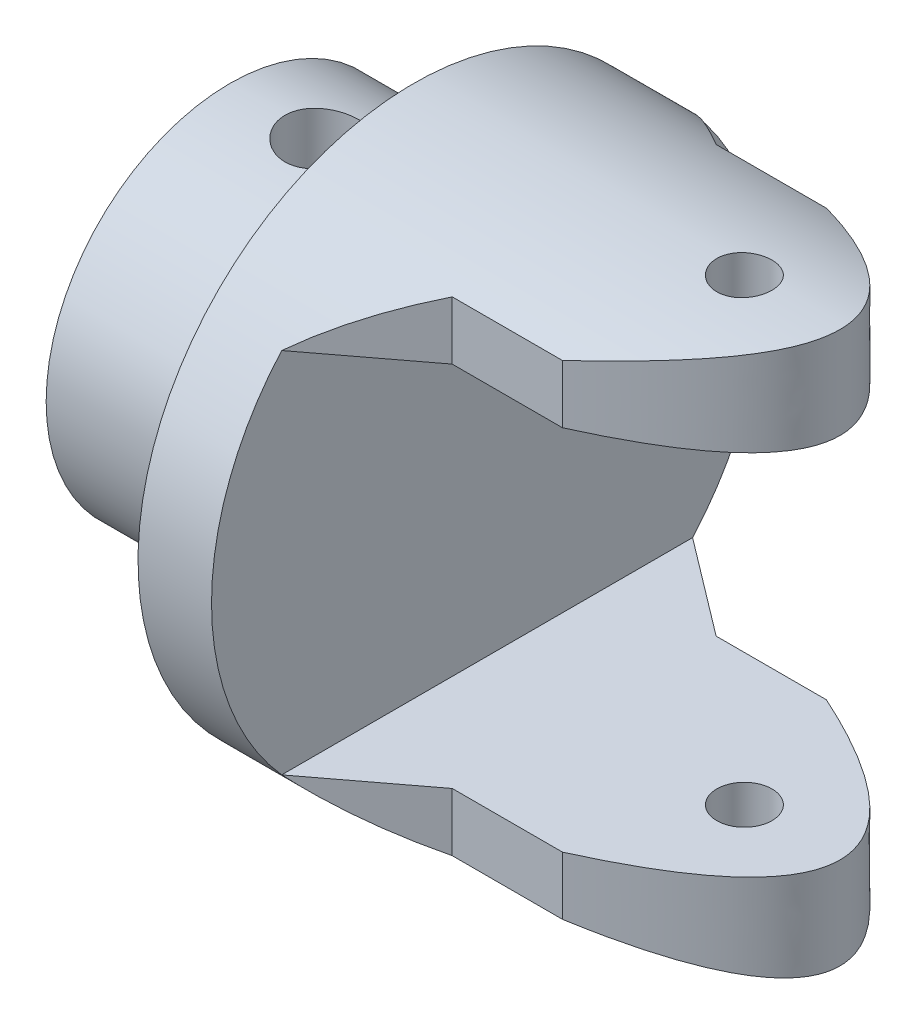
SolidWorks part; units mm, degrees
ref_plane "Front Plane" through (0, 0, 0) normal (0, 0, 1) x (1, 0, 0)
ref_plane "Top Plane" through (0, 0, 0) normal (0, 1, 0) x (1, 0, 0)
ref_plane "Right Plane" through (0, 0, 0) normal (1, 0, 0) x (0, 0, -1)
sketch "Sketch1" plane through (0, 0, 0) normal (1, 0, 0) x (0, 0, -1)
  circle A0 centre (0, 0) radius 5
  dimension "D1" = 10
extrude "Boss-Extrude1" add sketch "Sketch1" along normal blind 5
sketch "Sketch2" plane through (5, 0, 0) normal (1, 0, 0) x (0, 0, -1)
  circle A0 centre (0, 0) radius 7.5
  dimension "D1" = 15
extrude "Boss-Extrude2" add sketch "Sketch2" along normal blind 2
sketch "Sketch3" plane through (7, 0, 0) normal (1, 0, 0) x (0, 0, -1)
  line L1 (-5.5902, -5) -> (5.5902, -5)
  line L2 (-5.5902, -5) -> (-5.5902, 5)
  line L3 (-5.5902, 5) -> (5.5902, 5)
  line L4 (5.5902, -5) -> (5.5902, 5)
  line L5 (-5.5902, -5) -> (5.5902, 5) construction
  line L6 (-5.5902, 5) -> (5.5902, -5) construction
  arc A0 (-4.899, 5) -> (-4.899, -5) centre (0, 0) ccw
  circle A1 centre (0, 0) radius 7.5 construction
  arc A2 (4.899, -5) -> (4.899, 5) centre (0, 0) ccw
  point P0 (0, 0)
  circle M2 centre (0, 0) radius 7.5
  dimension "D1" = 10
extrude "Boss-Extrude3" add sketch "Sketch3" along normal blind 10 contours L3 M2 | L1 M2
sketch "Sketch4" plane through (0, 5, 0) normal (0, -1, 0) x (1, 0, 0)
  line L0 (17, 0) -> (5.8747, 0) construction
  line L1 (17, 5.5902) -> (17, -5.5902) construction
  line L7 (7, 5.5902) -> (17, 5.5902)
  line L8 (17, 5.5902) -> (17, -5.5902)
  line L9 (17, -5.5902) -> (7, -5.5902)
  line L10 (12.6404, 3.5902) -> (9.6404, 3.5902)
  line L11 (9.6404, 3.5902) -> (7, 5.5902)
  line L12 (12.6404, -3.5902) -> (9.6404, -3.5902)
  line L13 (9.6404, -3.5902) -> (7, -5.5902)
  spline S0 degree 3 poles (12.6404, -3.5902) (15.2801, -2.3934) (17.9199, 0) (15.2801, 2.3934) (12.6404, 3.5902) knots 0.178885 0.178885 0.178885 0.178885 0.5 0.821115 0.821115 0.821115 0.821115
  dimension "D1" = 9.6
  dimension "D2" = 3
  dimension "D3" = 2
  dimension "D4" = 3
  dimension "D5" = 2
extrude "Cut-Extrude1" cut sketch "Sketch4" against normal through all both and the other way through all
sketch "Sketch5" plane through (0, 5, 0) normal (0, -1, 0) x (1, 0, 0)
  line L0 (7, 0) -> (17.8474, 0) construction
  line L1 (7, 5.5902) -> (7, -5.5902) construction
  circle A0 centre (14, 0) radius 0.75
  dimension "D2" = 1.5
  dimension "D1" = 7
extrude "Cut-Extrude2" cut sketch "Sketch5" against normal through all both and the other way through all
sketch "Sketch6" plane through (0, 0, 0) normal (-1, 0, 0) x (0, 0, 1)
  circle A0 centre (0, 0) radius 2.5
  dimension "D1" = 5
extrude "Cut-Extrude3" cut sketch "Sketch6" against normal blind 5
sketch "Sketch7" plane through (0, 0, 0) normal (0, 1, 0) x (1, 0, 0)
  line L0 (0, 0) -> (17.9749, 0) construction
  line L1 (0, 5) -> (0, -5) construction
  circle A0 centre (2.5, 0) radius 1
  dimension "D2" = 2
  dimension "D1" = 2.5
extrude "Cut-Extrude4" cut sketch "Sketch7" against normal mid plane 20
